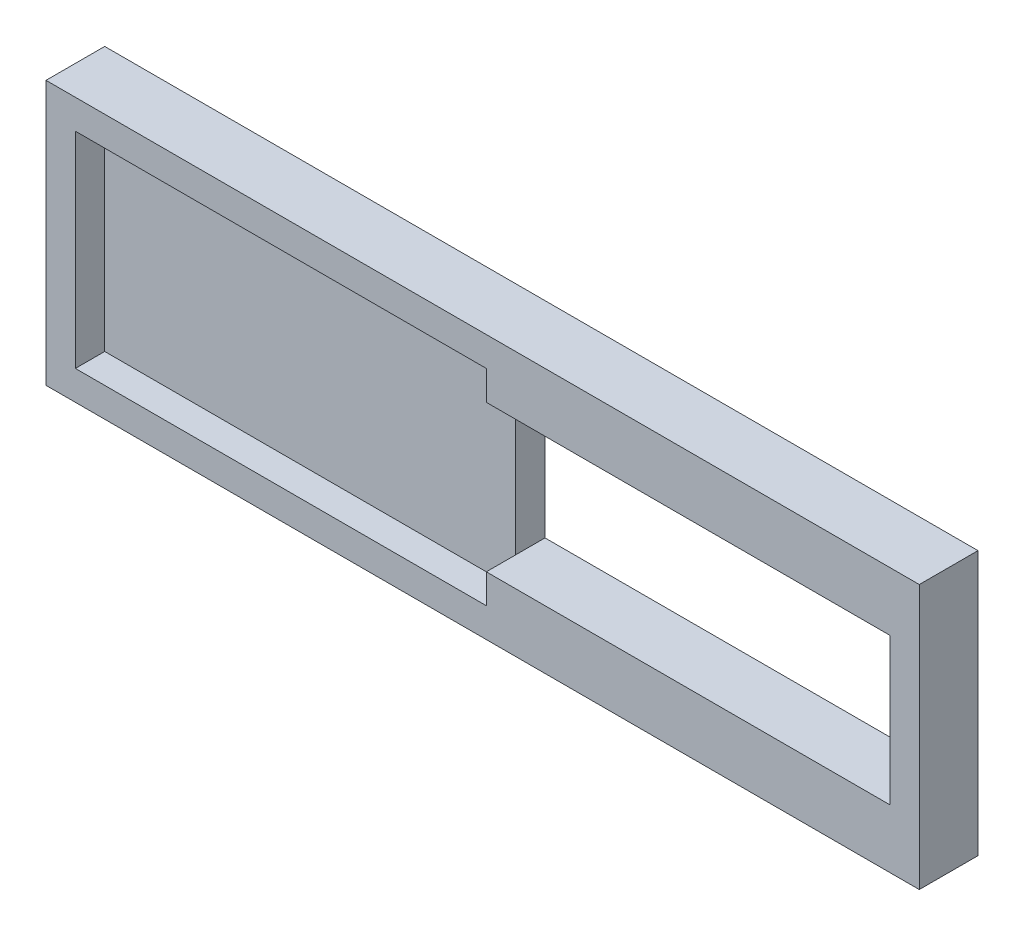
SolidWorks part; units mm, degrees
ref_plane "Front Plane" through (0, 0, 0) normal (0, 0, 1) x (1, 0, 0)
ref_plane "Top Plane" through (0, 0, 0) normal (0, 1, 0) x (1, 0, 0)
ref_plane "Right Plane" through (0, 0, 0) normal (1, 0, 0) x (0, 0, -1)
sketch "Sketch1" plane through (0, 0, 0) normal (0, 0, 1) x (1, 0, 0)
  line L1 (-37.7825, -11.43) -> (37.7825, -11.43)
  line L2 (-37.7825, -11.43) -> (-37.7825, 11.43)
  line L3 (-37.7825, 11.43) -> (37.7825, 11.43)
  line L4 (37.7825, -11.43) -> (37.7825, 11.43)
  line L5 (-37.7825, -11.43) -> (37.7825, 11.43) construction
  line L6 (-37.7825, 11.43) -> (37.7825, -11.43) construction
  point P0 (0, 0)
  dimension "D1" = 75.565
  dimension "D2" = 22.86
extrude "Boss-Extrude1" add sketch "Sketch1" along normal blind 5.08
sketch "Sketch2" plane through (0, 0, 5.08) normal (0, 0, 1) x (1, 0, 0)
  line L0 (-35.2425, 11.43) -> (-35.2425, 8.89) construction
  line L1 (37.7825, 11.43) -> (-37.7825, 11.43) construction
  line L2 (-35.2425, 8.89) -> (-37.7825, 8.89) construction
  line L3 (-37.7825, 11.43) -> (-37.7825, -11.43) construction
  line L5 (-35.2425, 8.89) -> (0.3175, 8.89)
  line L6 (-35.2425, 8.89) -> (-35.2425, -8.89)
  line L7 (-35.2425, -8.89) -> (0.3175, -8.89)
  line L8 (0.3175, 8.89) -> (0.3175, -8.89)
  dimension "D1" = 2.54
  dimension "D2" = 17.78
  dimension "D3" = 35.56
extrude "Cut-Extrude1" cut sketch "Sketch2" against normal blind 2.54
sketch "Sketch3" plane through (0, 0, 5.08) normal (0, 0, 1) x (1, 0, 0)
  line L0 (37.7825, 11.43) -> (35.2425, 11.43) construction
  line L1 (37.7825, 11.43) -> (-37.7825, 11.43) construction
  line L2 (35.2425, 11.43) -> (35.2425, 6.35) construction
  line L4 (35.2425, 6.35) -> (0.3175, 6.35)
  line L5 (35.2425, 6.35) -> (35.2425, -6.35)
  line L6 (35.2425, -6.35) -> (0.3175, -6.35)
  line L7 (0.3175, 6.35) -> (0.3175, -6.35)
  point P13 (0, 0)
  dimension "D1" = 5.08
  dimension "D2" = 12.7
  dimension "D3" = 34.925
  dimension "D4" = 2.54
extrude "Cut-Extrude2" cut sketch "Sketch3" against normal through all contours L4 L7 L6 L5
